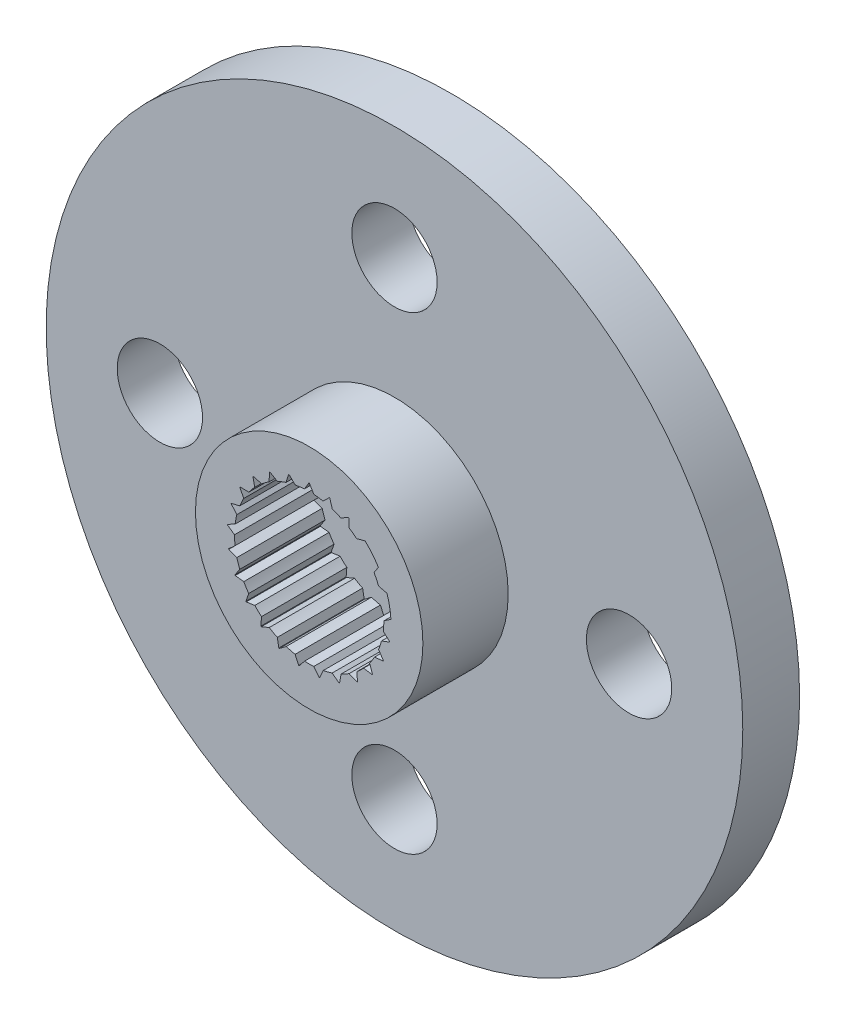
SolidWorks part; units mm, degrees
material "Alloy Steel (SS)"
ref_plane "Front Plane" through (0, 0, 0) normal (0, 0, 1) x (1, 0, 0)
ref_plane "Top Plane" through (0, 0, 0) normal (0, 1, 0) x (1, 0, 0)
ref_plane "Right Plane" through (0, 0, 0) normal (1, 0, 0) x (0, 0, -1)
sketch "Sketch1" plane through (0, 0, 0) normal (0, 0, 1) x (1, 0, 0)
  circle A0 centre (0, 0) radius 12.25
extrude "Boss-Extrude1" add sketch "Sketch1" along normal blind 2
sketch "Sketch2" plane through (0, 0, 2) normal (0, 0, 1) x (1, 0, 0)
  line L0 (-14.3323, 0) -> (13.8773, 0) construction
  line L1 (0, 13.8058) -> (0, -14.7886) construction
  circle A0 centre (-8.25, 0) radius 1.5
  circle A1 centre (0, 8.25) radius 1.5
  circle A2 centre (8.25, 0) radius 1.5
  circle A3 centre (0, -8.25) radius 1.5
  dimension "D2" = 4
  dimension "D1" = 8.25
extrude "Cut-Extrude1" cut sketch "Sketch2" against normal up to vertex (2 mm away) up to point (0, 0, 0)
sketch "Sketch3" plane through (0, 0, 2) normal (0, 0, 1) x (1, 0, 0)
  line L0 (-8.25, 0) -> (8.25, 0) construction
  line L1 (0, 8.25) -> (0, -8.25) construction
  circle A0 centre (0, 0) radius 1.35
extrude "Cut-Extrude2" cut sketch "Sketch3" against normal blind 4
sketch "Sketch4" plane through (0, 0, 2) normal (0, 0, 1) x (1, 0, 0)
  circle A0 centre (0, 0) radius 2.88
  circle A1 centre (0, 0) radius 4
extrude "Boss-Extrude2" add sketch "Sketch4" along normal blind 3
sketch "Sketch5" plane through (0, 0, 5) normal (0, 0, 1) x (1, 0, 0)
  line L0 (-0.3609, -2.8697) -> (-0.1618, -2.6206)
  line L2 (0.1625, -2.6206) -> (0.3617, -2.8696)
  line L3 (-0.3609, -2.8697) -> (0.3617, -2.8696) construction
  line L4 (0.0004, -2.8697) -> (0.0004, -2.6256) construction
  line L6 (-0.4943, -2.5787) -> (-0.3633, -2.8694)
  line L7 (-1.0633, -2.6898) -> (-0.8084, -2.4981)
  line L9 (-1.12, -2.3747) -> (-1.0655, -2.6889)
  line L10 (-1.6988, -2.3409) -> (-1.4042, -2.2185)
  line L12 (-1.6754, -2.0216) -> (-1.7007, -2.3394)
  line L13 (-2.2276, -1.8448) -> (-1.9118, -1.7996)
  line L15 (-2.1255, -1.5414) -> (-2.2291, -1.843)
  line L16 (-2.6164, -1.2329) -> (-2.2993, -1.2676)
  line L18 (-2.4421, -0.9644) -> (-2.6174, -1.2307)
  line L19 (-2.8408, -0.5435) -> (-2.5423, -0.656)
  line L21 (-2.6052, -0.3267) -> (-2.8412, -0.5411)
  line L22 (-2.8867, 0.18) -> (-2.6256, -0.0031)
  line L24 (-2.6046, 0.3314) -> (-2.8866, 0.1825)
  line L25 (-2.7512, 0.8923) -> (-2.5439, 0.6499)
  line L27 (-2.4404, 0.9687) -> (-2.7505, 0.8946)
  line L28 (-2.4429, 1.5484) -> (-2.3023, 1.2622)
  line L30 (-2.1228, 1.5452) -> (-2.4416, 1.5505)
  line L31 (-1.9811, 2.1073) -> (-1.9161, 1.7951)
  line L33 (-1.6718, 2.0246) -> (-1.9793, 2.109)
  line L34 (-1.3948, 2.5338) -> (-1.4095, 2.2152)
  line L36 (-1.1158, 2.3767) -> (-1.3926, 2.535)
  line L37 (-0.7208, 2.8011) -> (-0.8143, 2.4961)
  line L39 (-0.4897, 2.5795) -> (-0.7185, 2.8017)
  line L40 (-0.0016, 2.8923) -> (-0.168, 2.6202)
  line L42 (0.1672, 2.6203) -> (0.0008, 2.8923)
  line L43 (0.7178, 2.8018) -> (0.4889, 2.5797)
  line L45 (0.8136, 2.4964) -> (0.7201, 2.8012)
  line L46 (1.392, 2.5353) -> (1.1151, 2.377)
  line L48 (1.4088, 2.2156) -> (1.3941, 2.5341)
  line L49 (1.9788, 2.1095) -> (1.6712, 2.025)
  line L57 (2.5437, 0.6507) -> (2.751, 0.893)
  line L58 (2.8865, 0.1832) -> (2.6045, 0.3322)
  line L60 (2.6256, -0.0023) -> (2.8867, 0.1808)
  line L61 (2.8414, -0.5404) -> (2.6053, -0.326)
  line L63 (2.5425, -0.6552) -> (2.8409, -0.5428)
  line L64 (2.6177, -1.2301) -> (2.4424, -0.9637)
  line L66 (2.2997, -1.2669) -> (2.6167, -1.2323)
  line L67 (2.2296, -1.8424) -> (2.126, -1.5408)
  line L69 (1.9124, -1.7991) -> (2.228, -1.8443)
  line L70 (1.7013, -2.339) -> (1.676, -2.0211)
  line L72 (1.4049, -2.2181) -> (1.6994, -2.3404)
  line L73 (1.0662, -2.6886) -> (1.1207, -2.3744)
  line L75 (0.8091, -2.4978) -> (1.0639, -2.6895)
  line L76 (0.3641, -2.8693) -> (0.495, -2.5785)
  line L77 (2.282, 1.2985) -> (2.4425, 1.5491)
  line L78 (2.4412, 1.5511) -> (2.4425, 1.5491)
  line L79 (2.4395, 1.5511) -> (2.1223, 1.5458) [skipped]
  line L80 (1.9155, 1.7952) -> (1.9801, 2.1058) [skipped]
  line L81 (2.7486, 0.8957) -> (2.4401, 0.9694) [skipped]
  line L82 (1.9805, 2.1078) -> (1.9156, 1.7956)
  line L83 (2.4412, 1.5511) -> (2.1223, 1.5458)
  line L84 (2.751, 0.893) -> (2.441, 0.9671)
  line L85 (2.302, 1.2628) -> (2.4425, 1.5491) [skipped]
  arc A2 (-0.3609, -2.8697) -> (0.3617, -2.8696) centre (0, 0) ccw
  arc A3 (-1.0633, -2.6898) -> (-0.3633, -2.8694) centre (0, 0) ccw
  arc A4 (-1.6988, -2.3409) -> (-1.0655, -2.6889) centre (0, 0) ccw
  arc A5 (-2.2276, -1.8448) -> (-1.7007, -2.3394) centre (0, 0) ccw
  arc A6 (-2.6164, -1.2329) -> (-2.2291, -1.843) centre (0, 0) ccw
  arc A7 (-2.8408, -0.5435) -> (-2.6174, -1.2307) centre (0, 0) ccw
  arc A8 (-2.8867, 0.18) -> (-2.8412, -0.5411) centre (0, 0) ccw
  arc A9 (-2.7512, 0.8923) -> (-2.8866, 0.1825) centre (0, 0) ccw
  arc A10 (-2.4429, 1.5484) -> (-2.7505, 0.8946) centre (0, 0) ccw
  arc A11 (-1.9811, 2.1073) -> (-2.4416, 1.5505) centre (0, 0) ccw
  arc A12 (-1.3948, 2.5338) -> (-1.9793, 2.109) centre (0, 0) ccw
  arc A13 (-0.7208, 2.8011) -> (-1.3926, 2.535) centre (0, 0) ccw
  arc A14 (-0.0016, 2.8923) -> (-0.7185, 2.8017) centre (0, 0) ccw
  arc A15 (0.7178, 2.8018) -> (0.0008, 2.8923) centre (0, 0) ccw
  arc A16 (1.392, 2.5353) -> (0.7201, 2.8012) centre (0, 0) ccw
  arc A17 (1.9788, 2.1095) -> (1.3941, 2.5341) centre (0, 0) ccw
  arc A18 (2.4412, 1.5511) -> (1.9805, 2.1078) centre (0, 0) ccw
  arc A19 (2.7503, 0.8953) -> (2.4425, 1.5491) centre (0, 0) ccw
  arc A20 (2.8865, 0.1832) -> (2.751, 0.893) centre (0, 0) ccw
  arc A21 (2.8414, -0.5404) -> (2.8867, 0.1808) centre (0, 0) ccw
  arc A22 (2.6177, -1.2301) -> (2.8409, -0.5428) centre (0, 0) ccw
  arc A23 (2.2296, -1.8424) -> (2.6167, -1.2323) centre (0, 0) ccw
  arc A24 (1.7013, -2.339) -> (2.228, -1.8443) centre (0, 0) ccw
  arc A25 (1.0662, -2.6886) -> (1.6994, -2.3404) centre (0, 0) ccw
  arc A26 (0.3641, -2.8693) -> (1.0639, -2.6895) centre (0, 0) ccw
  circle A27 centre (0, 0) radius 2.6256
  dimension "D1" = 25
  dimension "D2" = 62.898
  dimension "D4" = 62.898
sketch "Sketch6" plane through (0, 0, 0) normal (0, 0, -1) x (-1, 0, 0)
  circle A0 centre (0, 0) radius 2
extrude "Cut-Extrude3" cut sketch "Sketch6" against normal blind 1
extrude "Boss-Extrude4" add sketch "Sketch5" against normal up to surface (3 mm away)
sketch "Sketch7" plane through (0, 0, 0) normal (0, 0, -1) x (-1, 0, 0)
  line L0 (0, 8.25) -> (0, -8.25) construction
  line L1 (-8.25, 0) -> (8.25, 0) construction
